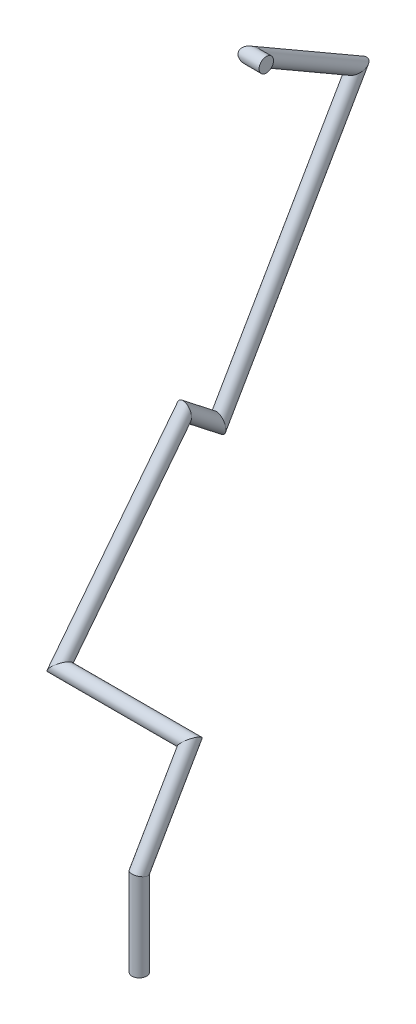
SolidWorks part; units mm, degrees
ref_plane "Front Plane" through (0, 0, 0) normal (0, 0, 1) x (1, 0, 0)
ref_plane "Top Plane" through (0, 0, 0) normal (0, 1, 0) x (1, 0, 0)
ref_plane "Right Plane" through (0, 0, 0) normal (1, 0, 0) x (0, 0, -1)
sketch3d "3DSketch1"
  line L0 (0, 0, 0) -> (0, 30, 0)
  line L1 (0, 30, 0) -> (0, 60.3109, -17.5)
  line L2 (0, 60.3109, -17.5) -> (-45, 60.3109, -17.5)
  line L3 (0, 60.3109, -17.5) -> (0, 124.4852, -67.6385) construction
  line L4 (-45, 60.3109, -17.5) -> (-45, 115.4716, -60.5963)
  line L5 (-45, 115.4716, -60.5963) -> (-45, 106.2367, -72.4165)
  line L6 (-45, 106.2367, -72.4165) -> (-45, 189.3752, -120.4165)
  line L7 (-45, 115.4716, -60.5963) -> (58.2879, 115.4716, -60.5963) construction
  line L8 (-45, 189.3752, -120.4165) -> (-45, 210.3752, -84.0434)
  line L9 (-45, 210.3752, -84.0434) -> (-40, 210.3752, -84.0434)
  point P11 (-49.4067, 73.3013, -25)
  point P12 (-79.8794, 196.3374, -102.7468)
  point P13 (-29.7534, 203.6072, -99.7658)
  dimension "D1" = 30
  dimension "D2" = 150
  dimension "D3" = 35
  dimension "D4" = 45
  dimension "D12" = 5
  dimension "D5" = 172
  dimension "D6" = 70
  dimension "D7" = 15
  dimension "D8" = 96
  dimension "D9" = 42
  dimension "D10" = 90
  dimension "D11" = 90
sweep "Sweep1" add path "3DSketch1" circular profile diameter 5 parameters "D3"=5
